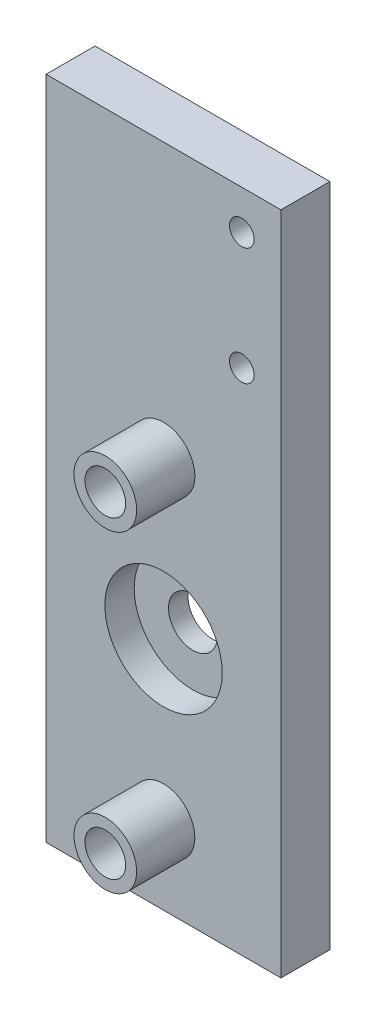
SolidWorks part; units mm, degrees
ref_plane "Front Plane" through (0, 0, 0) normal (0, 0, 1) x (1, 0, 0)
ref_plane "Top Plane" through (0, 0, 0) normal (0, 1, 0) x (1, 0, 0)
ref_plane "Right Plane" through (0, 0, 0) normal (1, 0, 0) x (0, 0, -1)
sketch "Sketch1" plane through (0, 0, 0) normal (0, 0, 1) x (1, 0, 0)
  line L1 (-19.05, -38.1) -> (19.05, -38.1)
  line L2 (-19.05, -38.1) -> (-19.05, 38.1)
  line L3 (-19.05, 38.1) -> (19.05, 38.1)
  line L4 (19.05, -38.1) -> (19.05, 38.1)
  line L5 (-19.05, -38.1) -> (19.05, 38.1) construction
  line L6 (-19.05, 38.1) -> (19.05, -38.1) construction
  point P0 (0, 0)
  dimension "D1" = 38.1
  dimension "D2" = 76.2
extrude "Boss-Extrude1" add sketch "Sketch1" along normal blind 7.9375
sketch "Sketch2" plane through (0, 0, 7.9375) normal (0, 0, 1) x (1, 0, 0)
  circle A0 centre (0, 0) radius 3.9688
  dimension "D1" = 7.9375
extrude "Cut-Extrude1" cut sketch "Sketch2" against normal through all
sketch "Sketch4" plane through (0, 0, 7.9375) normal (0, 0, 1) x (1, 0, 0)
  circle A0 centre (0, 0) radius 9.525
  dimension "D1" = 19.05
extrude "Cut-Extrude2" cut sketch "Sketch4" against normal offset from surface (4.7625 mm away) 3.175 up to face at (3.9688, 0, 0)
sketch "Sketch5" plane through (0, 0, 7.9375) normal (0, 0, 1) x (1, 0, 0)
  line L0 (19.05, 38.1) -> (-19.05, 38.1) construction
  circle A0 centre (0, 25.4) radius 5.08
  dimension "D1" = 10.16
  dimension "D2" = 12.7
extrude "Boss-Extrude2" add sketch "Sketch5" along normal blind 9.4488
sketch "Sketch6" plane through (0, 0, 17.3863) normal (0, 0, 1) x (1, 0, 0)
  circle A0 centre (0, 25.4) radius 3.302
  dimension "D1" = 6.604
extrude "Cut-Extrude3" cut sketch "Sketch6" against normal through all
mirror "Mirror1" about plane through (0, 0, 0) normal (0, 1, 0) of "Cut-Extrude3", "Boss-Extrude2"
sketch "Sketch7" plane through (0, 0, 7.9375) normal (0, 0, 1) x (1, 0, 0)
  line L0 (19.05, -38.1) -> (19.05, 38.1) construction
  line L1 (-19.05, 38.1) -> (19.05, 38.1)
  line L2 (-19.05, 38.1) -> (-19.05, 69.85)
  line L3 (-19.05, 69.85) -> (19.05, 69.85)
  line L4 (19.05, 38.1) -> (19.05, 69.85)
  line L5 (-19.05, 53.975) -> (19.05, 53.975) construction
  line L6 (12.7, 69.85) -> (12.7, 38.1) construction
  circle A0 centre (12.7, 63.5) radius 2
  circle A1 centre (12.7, 44.45) radius 2
  point P13 (0, 0)
  point P14 (0, 0)
  point P17 (12.7, 63.5)
  dimension "D4" = 4
  dimension "D1" = 31.75
  dimension "D2" = 9.525
  dimension "D3" = 6.35
extrude "Boss-Extrude4" add sketch "Sketch7" against normal up to surface (7.9375 mm away) up to face at (3.302, -25.4, 0)
